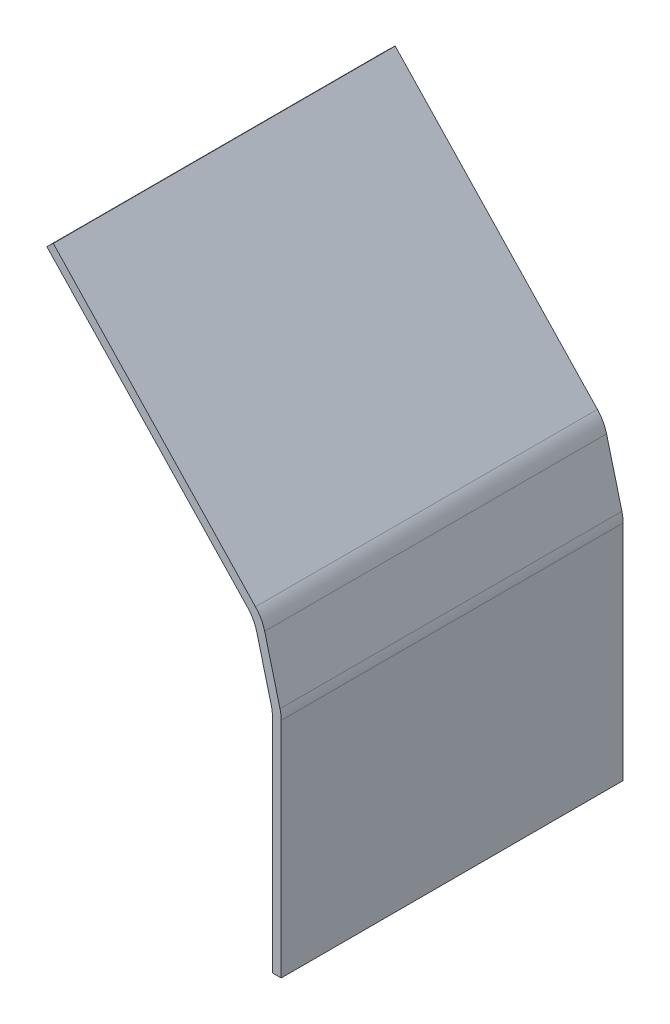
SolidWorks part; units mm, degrees
ref_plane "Front Plane" through (0, 0, 0) normal (0, 0, 1) x (1, 0, 0)
ref_plane "Top Plane" through (0, 0, 0) normal (0, 1, 0) x (1, 0, 0)
ref_plane "Right Plane" through (0, 0, 0) normal (1, 0, 0) x (0, 0, -1)
sketch "Sketch1" plane through (0, 0, 0) normal (1, 0, 0) x (0, 0, -1)
  line L1 (0, 0) -> (57.15, 0) construction
  line L2 (0, 0) -> (0, 101.6) construction
  line L3 (0, 101.6) -> (57.15, 101.6) construction
  line L4 (57.15, 0) -> (57.15, 101.6) construction
  circle A0 centre (10.922, 85.852) radius 4.9022
  circle A1 centre (27.686, 85.852) radius 4.9022
  circle A2 centre (44.45, 85.852) radius 4.9022
  circle A3 centre (27.686, 68.072) radius 4.9022
  circle A4 centre (44.45, 68.072) radius 4.9022
  circle A5 centre (27.686, 50.292) radius 4.9022
  circle A6 centre (44.45, 50.292) radius 4.9022
  circle A7 centre (27.686, 32.512) radius 4.9022
  circle A8 centre (44.45, 32.512) radius 4.9022
  circle A9 centre (27.686, 14.732) radius 4.9022
  circle A10 centre (44.45, 14.732) radius 4.9022
  circle A11 centre (10.922, 68.072) radius 4.9022
  circle A12 centre (10.922, 50.292) radius 4.9022
  circle A13 centre (10.922, 32.512) radius 4.9022
  circle A14 centre (10.922, 14.732) radius 4.9022
  dimension "D3" = 9.8044
  dimension "D4" = 15.748
  dimension "D5" = 10.922
  dimension "D1" = 57.15
  dimension "D2" = 101.6
  dimension "D6" = 3
  dimension "D7" = 5
sketch "Sketch2" plane through (0, 0, 0) normal (0, 0, 1) x (1, 0, 0)
  line L0 (0, 0) -> (0, 38.1)
  line L1 (0, 0) -> (0, 101.6) construction
  line L2 (-3.175, 50.3967) -> (-38.1, 87.2869)
  line L3 (-3.175, 50.3967) -> (0, 38.1)
  line L4 (-1.4732, 0) -> (-1.4732, 37.9129)
  line L5 (-4.5063, 49.6601) -> (-1.4732, 37.9129)
  line L6 (-4.5063, 49.6601) -> (-39.1698, 86.2741)
  line L7 (-39.1698, 86.2741) -> (-38.1, 87.2869)
  line L8 (-1.4732, 0) -> (0, 0)
  dimension "D3" = 12.7
  dimension "D1" = 38.1
  dimension "D2" = 50.8
  dimension "D4" = 38.1
  dimension "D5" = 34.925
  dimension "D6" = 1.4732
extrude "Boss-Extrude1" add sketch "Sketch2" against normal blind 57.15
fillet "Fillet1" radius 6.35 2 edges at (0, 38.1, -28.575) (-3.175, 50.3967, -28.575)
fillet "Fillet2" radius 6.35 2 edges at (-1.4732, 37.9129, -28.575) (-4.5063, 49.6601, -28.575)
